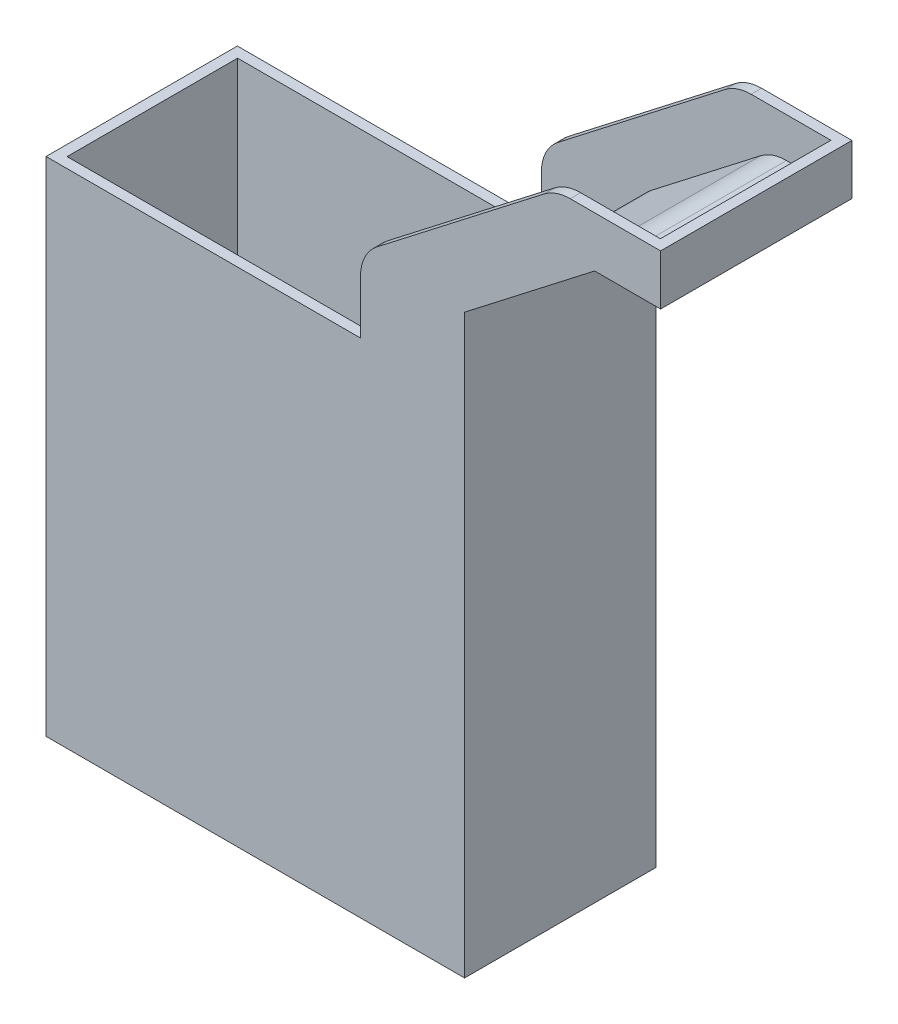
SolidWorks part; units mm, degrees
ref_plane "前视基准面" through (0, 0, 0) normal (0, 0, 1) x (1, 0, 0)
ref_plane "上视基准面" through (0, 0, 0) normal (0, 1, 0) x (1, 0, 0)
ref_plane "右视基准面" through (0, 0, 0) normal (1, 0, 0) x (0, 0, -1)
sketch "草图1" plane through (0, 0, 0) normal (0, 0, 1) x (1, 0, 0)
  line L0 (500, 0) -> (500, 88.9)
  line L1 (0, 0) -> (375.6881, 0)
  line L2 (0, 0) -> (0, -600)
  line L3 (0, -600) -> (500, -600)
  line L4 (500, 0) -> (500, -600)
  line L5 (500, 88.9) -> (655.4364, 209.2524)
  line L6 (655.4364, 209.2524) -> (734.2386, 209.2524)
  line L7 (734.2386, 209.2524) -> (734.2386, 269.4286)
  line L8 (734.2386, 269.4286) -> (608.8427, 269.4286)
  line L9 (608.8427, 269.4286) -> (375.6881, 88.9)
  line L10 (375.6881, 88.9) -> (375.6881, 0)
  dimension "D1" = 600
  dimension "D2" = 500
  dimension "D3" = 88.9
extrude "凸台-拉伸1" add sketch "草图1" along normal mid plane 228.6
sketch "草图2" plane through (0, 0, 0) normal (0, 0, 1) x (1, 0, 0)
  line L10 (12.7, -12.7) -> (12.7, 37.1788)
  line L11 (12.7, 37.1788) -> (353.8725, 37.1788)
  line L12 (353.8725, 37.1788) -> (353.8725, 355.9738)
  line L13 (353.8725, 355.9738) -> (721.5386, 346.8224)
  line L14 (721.5386, 346.8224) -> (721.5386, 256.7286)
  line L20 (12.7, -12.7) -> (12.7, -587.3)
  line L21 (12.7, -587.3) -> (487.3, -587.3)
  line L22 (487.3, -587.3) -> (487.3, 95.1285)
  line L23 (487.3, 95.1285) -> (651.0944, 221.9524)
  line L24 (651.0944, 221.9524) -> (721.5386, 221.9524)
  line L25 (721.5386, 221.9524) -> (721.5386, 256.7286)
  line L26 (721.5386, 256.7286) -> (613.1847, 256.7286)
  line L27 (613.1847, 256.7286) -> (388.3881, 82.6715)
  line L28 (388.3881, 82.6715) -> (388.3881, -12.7)
  line L29 (388.3881, -12.7) -> (12.7, -12.7)
  line L30 (12.7, -12.7) -> (12.7, -587.3)
  line L31 (12.7, -587.3) -> (487.3, -587.3)
  line L32 (487.3, -587.3) -> (487.3, 95.1285)
  line L33 (487.3, 95.1285) -> (651.0944, 221.9524)
  line L34 (651.0944, 221.9524) -> (721.5386, 221.9524)
  line L35 (721.5386, 221.9524) -> (721.5386, 256.7286)
  dimension "D1" = 12.7
extrude "切除-拉伸1" cut sketch "草图2" against normal mid plane 203.708
fillet "圆角2" radius 50.8 1 edges at (487.3, 95.1285, 0)
fillet "圆角3" radius 50.8 1 edges at (651.0944, 221.9524, 0)
fillet "圆角4" radius 50.8 2 edges at (608.8427, 269.4286, -108.077) (608.8427, 269.4286, 108.077)
fillet "圆角5" radius 50.8 2 edges at (375.6881, 88.9, 108.077) (375.6881, 88.9, -108.077)
